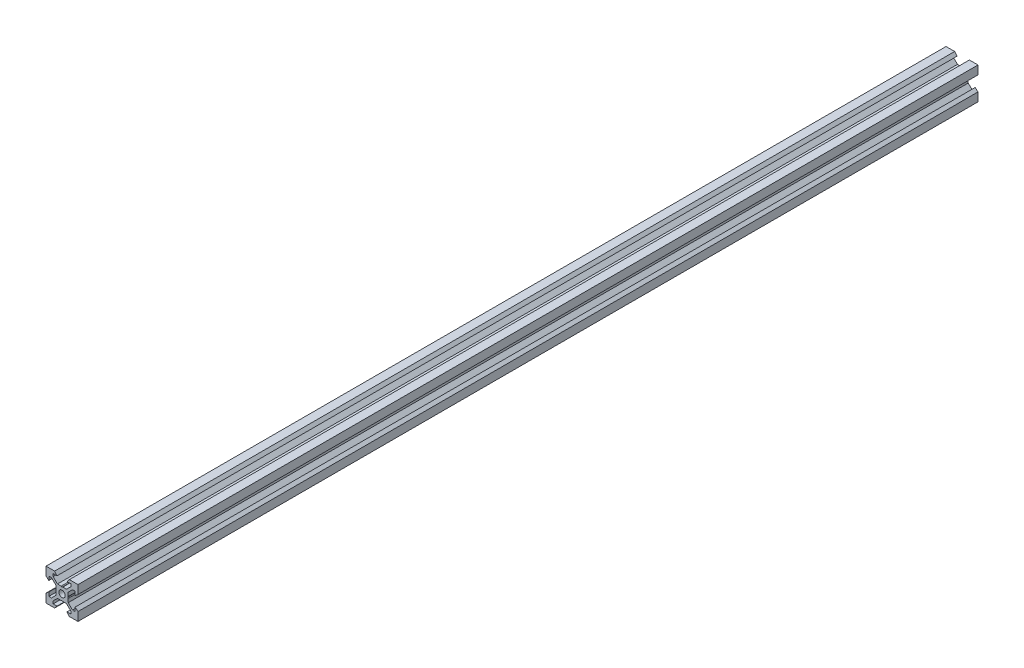
SolidWorks part; units mm, degrees
ref_plane "Front Plane" through (0, 0, 0) normal (0, 0, 1) x (1, 0, 0)
ref_plane "Top Plane" through (0, 0, 0) normal (0, 1, 0) x (1, 0, 0)
ref_plane "Right Plane" through (0, 0, 0) normal (1, 0, 0) x (0, 0, -1)
sketch "Sketch1" plane through (0, 0, 0) normal (0, 0, 1) x (1, 0, 0)
  line L0 (10, 10) -> (4.6104, 10) construction
  line L1 (10, 10) -> (10, 4.6104) construction
  line L2 (10, -10) -> (10, -4.6104) construction
  line L3 (10, -10) -> (4.6104, -10) construction
  line L4 (10, 10) -> (10, 4.6104)
  line L5 (6.5607, 5.5) -> (8.2, 5.5)
  line L6 (5.5, 8.2) -> (5.5, 6.5607)
  line L7 (10, 10) -> (4.6104, 10)
  line L8 (10, 10) -> (10, 4.6104)
  line L9 (6.5607, 5.5) -> (3.9, 2.8393)
  line L10 (5.5, 6.5607) -> (2.8393, 3.9)
  line L11 (10, 4.6104) -> (8.2, 3.1)
  line L12 (4.6104, 10) -> (3.1, 8.2)
  line L13 (8.2, 3.1) -> (8.2, 5.5)
  line L14 (3.1, 8.2) -> (5.5, 8.2)
  line L15 (-6.5607, 5.5) -> (-8.2, 5.5)
  line L16 (6.5607, -5.5) -> (8.2, -5.5)
  line L17 (3.1, -8.2) -> (5.5, -8.2)
  line L18 (8.2, -3.1) -> (8.2, -5.5)
  line L19 (4.6104, -10) -> (3.1, -8.2)
  line L20 (10, -4.6104) -> (8.2, -3.1)
  line L21 (0.5196, -3.9) -> (0, -3.6)
  line L22 (0.5196, 3.9) -> (0, 3.6)
  line L23 (3.6, 0) -> (3.9, -0.5196)
  line L24 (3.9, 0.5196) -> (3.6, 0)
  line L25 (3.9, 0.5196) -> (3.9, 2.8393)
  line L26 (2.8393, 3.9) -> (0.5196, 3.9)
  line L27 (3.9, -2.8393) -> (3.9, -0.5196)
  line L28 (2.8393, -3.9) -> (0.5196, -3.9)
  line L29 (5.5, -6.5607) -> (2.8393, -3.9)
  line L30 (6.5607, -5.5) -> (3.9, -2.8393)
  line L31 (10, -10) -> (10, -4.6104)
  line L32 (10, -10) -> (4.6104, -10)
  line L33 (5.5, -8.2) -> (5.5, -6.5607)
  line L34 (-6.5607, -5.5) -> (-8.2, -5.5)
  line L35 (10, -10) -> (10, -4.6104)
  line L36 (0, 0) -> (0, 8.2) construction
  line L37 (-10, -10) -> (-4.6104, -10) construction
  line L38 (-10, -10) -> (-10, -4.6104) construction
  line L39 (-10, 10) -> (-10, 4.6104) construction
  line L40 (-10, 10) -> (-4.6104, 10) construction
  line L41 (-10, -10) -> (-10, -4.6104)
  line L43 (-5.5, -8.2) -> (-5.5, -6.5607)
  line L44 (-10, -10) -> (-4.6104, -10)
  line L45 (-10, -10) -> (-10, -4.6104)
  line L46 (-6.5607, -5.5) -> (-3.9, -2.8393)
  line L47 (-5.5, -6.5607) -> (-2.8393, -3.9)
  line L48 (-2.8393, -3.9) -> (-0.5196, -3.9)
  line L49 (-3.9, -2.8393) -> (-3.9, -0.5196)
  line L50 (-2.8393, 3.9) -> (-0.5196, 3.9)
  line L51 (-3.9, 0.5196) -> (-3.9, 2.8393)
  line L52 (-3.9, 0.5196) -> (-3.6, 0)
  line L53 (-3.6, 0) -> (-3.9, -0.5196)
  line L54 (-0.5196, 3.9) -> (0, 3.6)
  line L55 (-0.5196, -3.9) -> (0, -3.6)
  line L56 (-10, -4.6104) -> (-8.2, -3.1)
  line L57 (-4.6104, -10) -> (-3.1, -8.2)
  line L58 (-8.2, -3.1) -> (-8.2, -5.5)
  line L59 (-3.1, -8.2) -> (-5.5, -8.2)
  line L60 (-10, -10) -> (10, -10) construction
  line L61 (-10, -10) -> (-10, 10) construction
  line L62 (-3.1, 8.2) -> (-5.5, 8.2)
  line L63 (-8.2, 3.1) -> (-8.2, 5.5)
  line L64 (-4.6104, 10) -> (-3.1, 8.2)
  line L65 (-10, 4.6104) -> (-8.2, 3.1)
  line L66 (-5.5, 6.5607) -> (-2.8393, 3.9)
  line L67 (-6.5607, 5.5) -> (-3.9, 2.8393)
  line L68 (-10, 10) -> (-10, 4.6104)
  line L69 (-10, 10) -> (-4.6104, 10)
  line L70 (-5.5, 8.2) -> (-5.5, 6.5607)
  line L71 (-10, 10) -> (10, 10) construction
  line L72 (-10, 10) -> (-10, 4.6104)
  line L73 (10, -10) -> (10, 10) construction
  line L74 (-10, -10) -> (10, 10) construction
  line L75 (-10, 10) -> (10, -10) construction
  circle A0 centre (0, 0) radius 2
  dimension "D7" = 4
  dimension "D1" = 20
  dimension "D2" = 5.3896
  dimension "D3" = 4.5
  dimension "D4" = 50
  dimension "D5" = 1.8
  dimension "D6" = 1.5104
  dimension "D8" = 5.5
  dimension "D9" = 120
  dimension "D10" = 0.3
  dimension "D11" = 2.3197
  dimension "D12" = 7.8
  dimension "D13" = 7.8
  dimension "D14" = 1.5
  dimension "D15" = 2.6607
extrude "Boss-Extrude1" add sketch "Sketch1" along normal mid plane 563 contours L70 L62 L64 L69 L68 L65 L63 L15 L67 L51 L52 L53 L49 L46 L34 L58 L56 L41 L44 L57 L59 L43 L47 L48 L55 L21 L28 L29 L33 L17 L19 L32 L31 L20 L18 L16 L30 L27 L23 L24 L25 L9 L5 L13 L11 L4 L7 L12 L14 L6 L10
